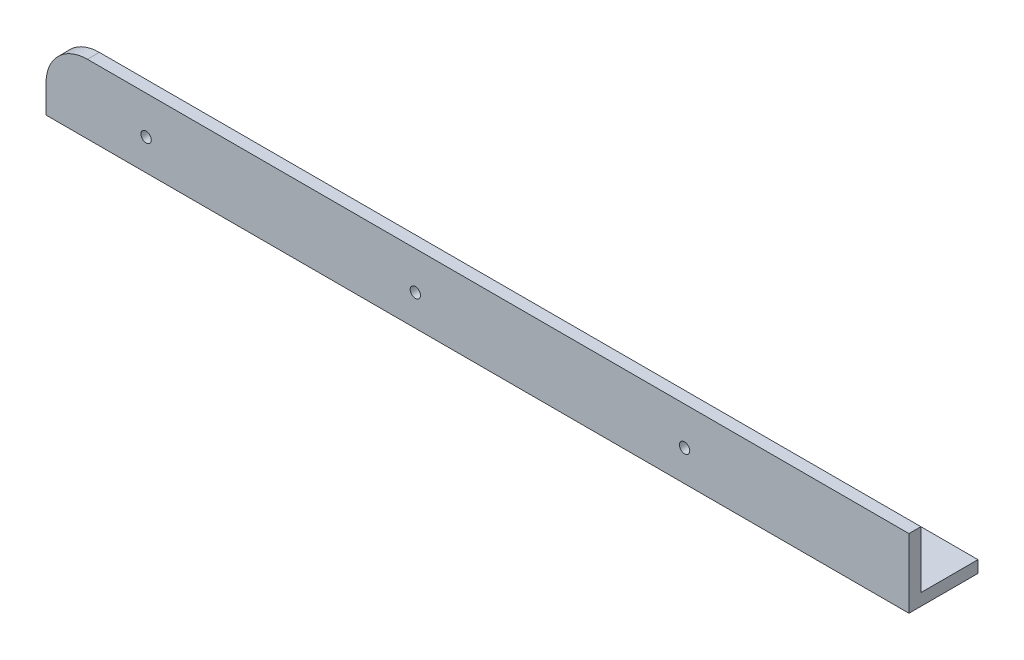
SolidWorks part; units mm, degrees
ref_plane "Front Plane" through (0, 0, 0) normal (0, 0, 1) x (1, 0, 0)
ref_plane "Top Plane" through (0, 0, 0) normal (0, 1, 0) x (1, 0, 0)
ref_plane "Right Plane" through (0, 0, 0) normal (1, 0, 0) x (0, 0, -1)
sketch "Sketch1" plane through (0, 0, 0) normal (1, 0, 0) x (0, 0, -1)
  line L0 (0, 0) -> (20, 0)
  line L1 (20, 0) -> (20, 3.4612)
  line L2 (20, 3.4612) -> (3.4612, 3.4612)
  line L3 (3.4612, 3.4612) -> (3.4612, 20)
  line L4 (3.4612, 20) -> (0, 20)
  line L5 (0, 20) -> (0, 0)
  dimension "D1" = 3.4612
  dimension "D2" = 20
extrude "Boss-Extrude1" add sketch "Sketch1" along normal blind 250
sketch "Sketch2" plane through (0, 0, 0) normal (0, -1, 0) x (1, 0, 0)
  line L0 (0, 0) -> (20, -20)
  line L1 (250, -20) -> (0, -20) construction
  line L2 (20, -20) -> (0, -20)
  line L3 (0, -20) -> (0, 0)
  line L4 (250, -10) -> (10, -10) construction
  line L5 (250, 0) -> (250, -20) construction
  circle A0 centre (130, -10) radius 1.5
  circle A1 centre (34, -10) radius 1.5
  circle A2 centre (226, -10) radius 1.5
  dimension "D1" = 3
  dimension "D2" = 96
  dimension "D3" = 96
extrude "Cut-Extrude1" cut sketch "Sketch2" against normal through all
sketch "Sketch3" plane through (0, 0, 0) normal (0, 0, 1) x (1, 0, 0)
  line L0 (12, 20) -> (0, 20)
  line L1 (0, 20) -> (0, 8)
  arc A1 (12, 20) -> (0, 8) centre (12, 8) ccw construction
  circle A2 centre (29, 9) radius 1.5 construction
  circle A3 centre (107, 9) radius 1.5 construction
  circle A4 centre (185, 9) radius 1.5 construction
  arc A5 (12, 20) -> (0, 8) centre (12, 8) ccw
  circle A6 centre (29, 9) radius 1.5
  circle A7 centre (107, 9) radius 1.5
  circle A8 centre (185, 9) radius 1.5
extrude "Cut-Extrude2" cut sketch "Sketch3" against normal through all
